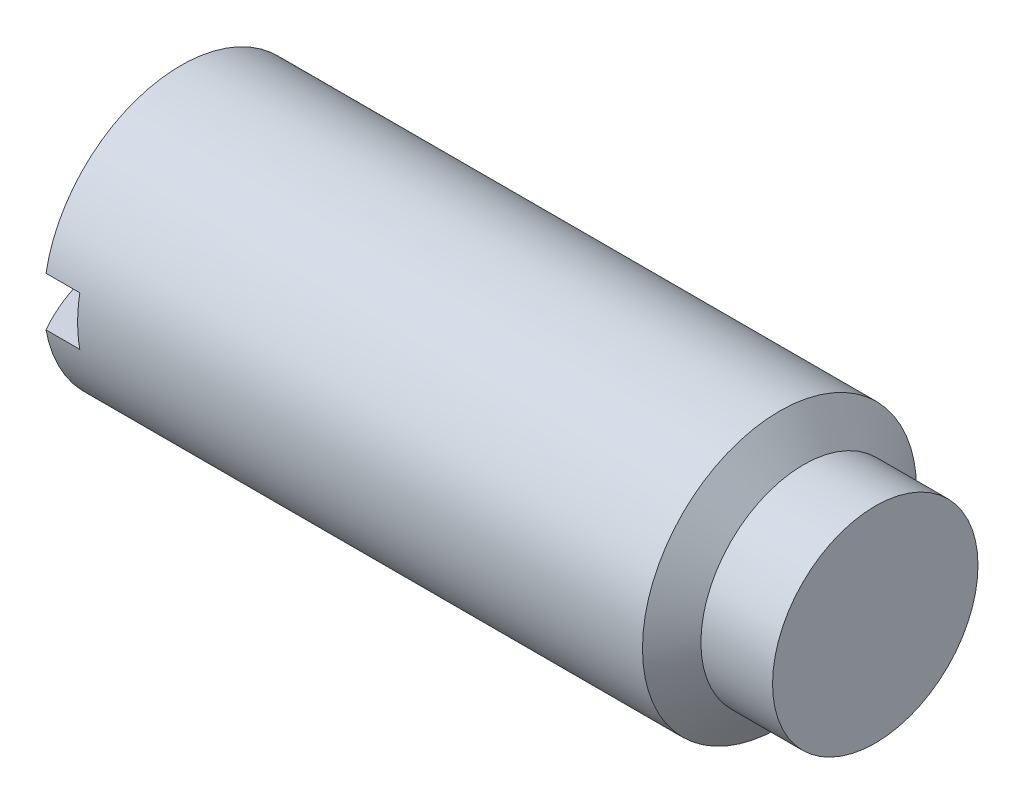
SolidWorks part; units mm, degrees
revolve "BaseBody" add sketch "BodySke" angle 360 about L5
sketch "BodySke" plane through (0, 0, 0) normal (0, 0, 1) x (1, 0, 0)
  line L0 (2.5522, -9.525) -> (19.05, -9.525) construction
  line L1 (45.8216, 7.1374) -> (50.8, 7.1374)
  line L2 (2.5522, 9.525) -> (44.1498, 9.525)
  line L3 (45.8216, 7.1374) -> (44.1498, 9.525)
  line L4 (50.8, 0) -> (0, 0)
  line L5 (-12.7, 0) -> (88.9, 0) construction
  line L6 (2.0066, 12.7) -> (2.0066, -3.175) construction
  line L7 (50.8, 7.1374) -> (50.8, 0)
  line L8 (45.8216, -7.1374) -> (50.8, -7.1374) construction
  arc A1 (2.5522, 9.525) -> (0, 0) centre (19.05, 0) ccw
  dimension "Crown_radius" = 19.05
  dimension "Diameter" = 19.05
  dimension "Dog_dia" = 14.2748
  dimension "D1" = 125
  dimension "Length" = 50.8
  dimension "Dog_len" = 4.9784
  dimension "Advance" = 2.0066
cosmetic thread "ThreadCosmetic" [suppressed] parameters "Thread_minor"=16.0249
extrude "Slot" cut sketch "Sketch2" along normal blind 4.9022
sketch "Sketch2" plane through (0, 0, 0) normal (1, 0, 0) x (0, 0, -1)
  line L1 (9.525, -1.7018) -> (-9.525, -1.7018)
  line L2 (9.525, -1.7018) -> (9.525, 1.7018)
  line L3 (9.525, 1.7018) -> (-9.525, 1.7018)
  line L4 (-9.525, -1.7018) -> (-9.525, 1.7018)
  dimension "D1" = 19.05
  dimension "Slot_width" = 3.4036
  dimension "D3" = 9.525
  dimension "D2" = 1.7018
ref_plane "Plane1" through (0, 0, 0) normal (0, 0, 1) x (1, 0, 0)
ref_plane "Plane2" through (0, 0, 0) normal (0, 1, 0) x (1, 0, 0)
ref_plane "Plane3" through (0, 0, 0) normal (1, 0, 0) x (0, 0, -1)
sketch "ThdSchSke" plane through (0, 0, 0) normal (0, 0, 1) x (1, 0, 0)
  line L0 (2.5522, -8.0124) -> (1.4931, -9.525)
  line L1 (2.5522, -8.0124) -> (3.6113, -9.525)
  line L2 (3.6113, -9.525) -> (3.6113, -11.9063)
  line L3 (-3.175, 0) -> (5.1513, 0) construction
  line L4 (2.5522, -9.525) -> (2.5522, -1.7018) construction
  line L5 (3.6113, -11.9063) -> (1.4931, -11.9063)
  line L6 (1.4931, -11.9063) -> (1.4931, -9.525)
  dimension "Diameter" = 19.05
  dimension "Thread_minor" = 16.0249
revolve "ThreadSchematic" [suppressed] cut sketch "ThdSchSke" angle 360 about L3
pattern_linear "ThdSchPat" [suppressed]
equation "\"D1@Sketch2\" = \"Diameter@BodySke\""
equation "\"D3@Sketch2\" = \"D1@Sketch2\" / 2"
equation "\"D2@Sketch2\" = \"Slot_width@Sketch2\" / 2"
equation "\"Thread_minor@ThdSchSke\" = \"Thread_minor@ThreadCosmetic\""
equation "\"Diameter@ThdSchSke\" = \"Diameter@BodySke\""
equation "\"Overcut@ThdSchSke\" = \"Diameter@BodySke\" * 1.25"
equation "\"Num_threads@ThdSchPat\" = int ( ( \"Length@BodySke\" - ( \"Crown_radius@BodySke\" - sqr ( ( \"Crown_radius@BodySke\" * \"Crown_radius@BodySke\" ) - ( ( \"Diameter@BodySke\" * 0.5 ) * ( \"Diameter@BodySke\" * 0.5 ) ) ) ) - \"Dog_len@BodySke\" ) / \"Advance@BodySke\" + 0.999 )  + 1"
equation "\"Advance@ThdSchPat\" = ( \"Length@BodySke\" - ( \"Crown_radius@BodySke\" - sqr ( ( \"Crown_radius@BodySke\" * \"Crown_radius@BodySke\" ) - ( ( \"Diameter@BodySke\" * 0.5 ) * ( \"Diameter@BodySke\" * 0.5 ) ) ) ) - \"Dog_len@BodySke\" ) /  (\"Num_threads@ThdSchPat\" - 1) 'relax it"
equation "\"Num_threads@ThdSchPat\" = \"Num_threads@ThdSchPat\" - sgn( \"Num_threads@ThdSchPat\" - 1) '---chamfered tips only---"
